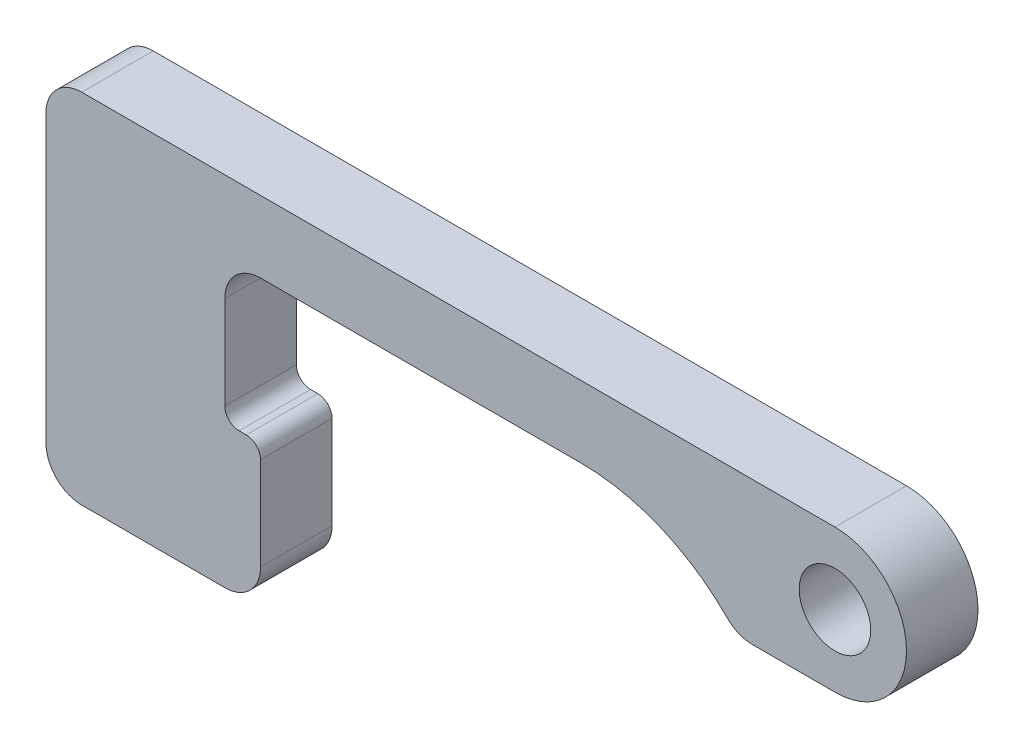
SolidWorks part; units mm, degrees
ref_plane "Front Plane" through (0, 0, 0) normal (0, 0, 1) x (1, 0, 0)
ref_plane "Top Plane" through (0, 0, 0) normal (0, 1, 0) x (1, 0, 0)
ref_plane "Right Plane" through (0, 0, 0) normal (1, 0, 0) x (0, 0, -1)
sketch "Sketch1" plane through (0, 0, 0) normal (0, 0, 1) x (1, 0, 0)
  line L0 (-80.3169, -40) -> (-110.3169, -40)
  line L1 (-110.3169, -40) -> (-110.3169, 10)
  line L2 (-110.3169, 10) -> (0, 10)
  line L4 (0, -10) -> (-13.704, -10)
  line L6 (-85.3169, 0) -> (-85.3169, -20)
  line L7 (-85.3169, -20) -> (-80.3169, -20)
  line L8 (-80.3169, -20) -> (-80.3169, -40)
  line L10 (-85.3169, 0) -> (-35.5537, 0)
  arc A1 (-13.704, -10) -> (-35.5537, 0) centre (-35.5537, -28.8705) ccw
  circle A3 centre (0, 0) radius 5
  arc A4 (0, -10) -> (0, 10) centre (0, 0) ccw
  dimension "D5" = 10
  dimension "D6" = 20
  dimension "D1" = 25
  dimension "D2" = 5
  dimension "D3" = 20
  dimension "D4" = 20
  dimension "D7" = 49.7632
  dimension "D8" = 10
  dimension "D9" = 110.3169
  dimension "D10" = 21.8497
extrude "Boss-Extrude1" add sketch "Sketch1" along normal blind 10
fillet "Fillet1" radius 5 5 edges at (-13.704, -10, 5) (-110.3169, 10, 5) (-80.3169, -40, 5) (-110.3169, -40, 5) (-85.3169, 0, 5)
fillet "Fillet2" radius 2 2 edges at (-85.3169, -20, 5) (-80.3169, -20, 5)
